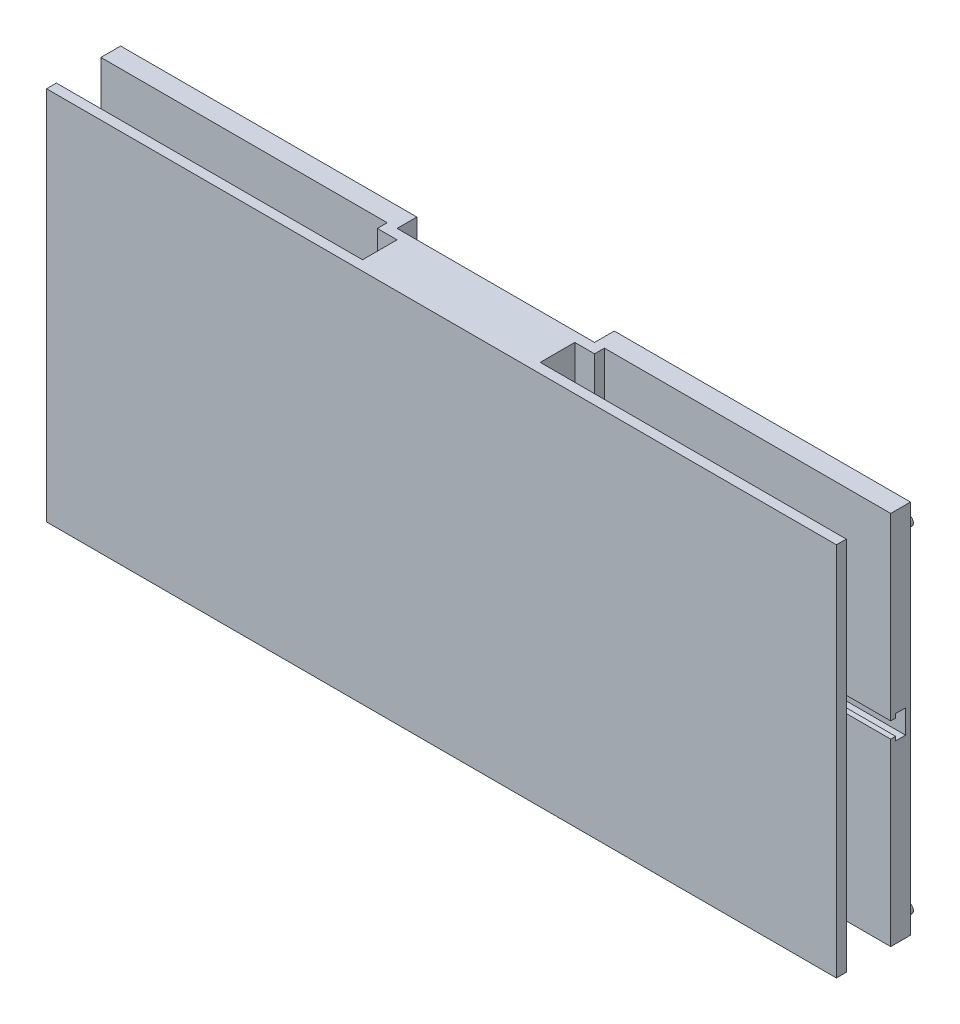
SolidWorks part; units mm, degrees
ref_plane "Front Plane" through (0, 0, 0) normal (0, 0, 1) x (1, 0, 0)
ref_plane "Top Plane" through (0, 0, 0) normal (0, 1, 0) x (1, 0, 0)
ref_plane "Right Plane" through (0, 0, 0) normal (1, 0, 0) x (0, 0, -1)
sketch "Sketch1" plane through (0, 0, 0) normal (0, 0, 1) x (1, 0, 0)
  line L1 (-15, -19) -> (15, -19)
  line L2 (-15, -19) -> (-15, 19)
  line L3 (-15, 19) -> (15, 19)
  line L4 (15, -19) -> (15, 19)
  line L5 (-15, -19) -> (15, 19) construction
  line L6 (-15, 19) -> (15, -19) construction
  point P0 (0, 0)
  dimension "D1" = 38
  dimension "D2" = 30
extrude "Boss-Extrude1" add sketch "Sketch1" along normal blind 2 contours L4 L3 L2 L1
sketch "Sketch2" plane through (0, 0, 0) normal (0, 0, -1) x (-1, 0, 0)
  line L0 (15, 19) -> (-15, 19) construction
  line L1 (15, -19) -> (15, 19) construction
  line L2 (14, 16.5) -> (14, -19) construction
  line L4 (15, -19) -> (-15, -19) construction
  circle A0 centre (14, 16.5) radius 0.5
  circle A2 centre (14, -17.5) radius 0.5
  dimension "D3" = 1
  dimension "D5" = 1
  dimension "D1" = 2.5
  dimension "D2" = 1
  dimension "D4" = 1.5
extrude "Boss-Extrude2" add sketch "Sketch2" along normal blind 0.8
sketch "Sketch5" plane through (0, 0, 2) normal (0, 0, 1) x (1, 0, 0)
  line L0 (-15, -19) -> (15, -19) construction
  line L1 (15, 19) -> (14, 19)
  line L2 (15, 19) -> (15, -19)
  line L3 (15, -19) -> (14, -19)
  line L4 (14, 19) -> (14, -19)
  dimension "D1" = 1
extrude "Boss-Extrude4" add sketch "Sketch5" along normal blind 1
sketch "Sketch6" plane through (15, 0, 0) normal (1, 0, 0) x (0, 0, -1)
  line L0 (-3, -19) -> (0, -19) construction
  line L1 (-3, 19) -> (-2, 19)
  line L2 (-3, 19) -> (-3, -19)
  line L3 (-3, -19) -> (-2, -19)
  line L4 (-2, 19) -> (-2, -19)
  dimension "D1" = 1
extrude "Boss-Extrude5" add sketch "Sketch6" along normal blind 20
sketch "Sketch7" plane through (0, 19, 0) normal (0, 1, 0) x (1, 0, 0)
  line L0 (25, -2) -> (25, -3) construction
  line L1 (35, -2) -> (15, -2) construction
  line L2 (35, -3) -> (14, -3) construction
ref_plane "Plane2" through (25, 0, 0) normal (1, 0, 0) x (0, 0, -1)
mirror "Mirror2" about plane through (25, 0, 0) normal (1, 0, 0) of bodies 106
sketch "Sketch8" plane through (0, 0, 3) normal (0, 0, 1) x (1, 0, 0)
  line L0 (14, -19) -> (36, -19) construction
  line L1 (16, -19) -> (34, -19)
  line L2 (16, -19) -> (16, 19)
  line L3 (16, 19) -> (34, 19)
  line L4 (34, -19) -> (34, 19)
  line L5 (36, 19) -> (14, 19) construction
  line L6 (14, 19) -> (14, -19) construction
  line L7 (36, 19) -> (36, -19) construction
  dimension "D1" = 2
  dimension "D2" = 2
extrude "Boss-Extrude6" add sketch "Sketch8" along normal blind 3.5
sketch "Sketch9" plane through (-15, 0, 0) normal (-1, 0, 0) x (0, 0, 1)
  line L0 (2, -0.8) -> (2, 0.8)
  line L1 (2, 19) -> (2, -19) construction
  line L2 (2, 0.8) -> (1.5, 0.8)
  line L3 (1.5, 0.8) -> (1.5, 1.2)
  line L4 (1.5, 1.2) -> (0.5, 1.2)
  line L5 (0.5, 1.2) -> (0.5, -1.2)
  line L7 (1.5, -1.2) -> (0.5, -1.2)
  line L8 (1.5, -0.8) -> (1.5, -1.2)
  line L9 (2, -0.8) -> (1.5, -0.8)
  line L10 (2, -19) -> (0, -19) construction
  point P0 (2, 0)
  dimension "D1" = 1.6
  dimension "D2" = 0.5
  dimension "D3" = 1
  dimension "D4" = 2.4
  dimension "D5" = 0.4
  dimension "D6" = 19
  dimension "D7" = 0.5
  dimension "D8" = 1
extrude "Cut-Extrude1" cut sketch "Sketch9" against normal up to vertex (29 mm away) contours L4 L5 L7 L8 L9 L0 L2 L3
mirror "Mirror3" about plane through (25, 0, 0) normal (1, 0, 0) of "Cut-Extrude1"
sketch "Sketch12" plane through (0, 0, 6.5) normal (0, 0, 1) x (1, 0, 0)
  line L1 (65, -19) -> (-15, -19)
  line L2 (65, -19) -> (65, 19)
  line L3 (65, 19) -> (-15, 19)
  line L4 (-15, -19) -> (-15, 19)
extrude "Boss-Extrude7" add sketch "Sketch12" along normal blind 1
